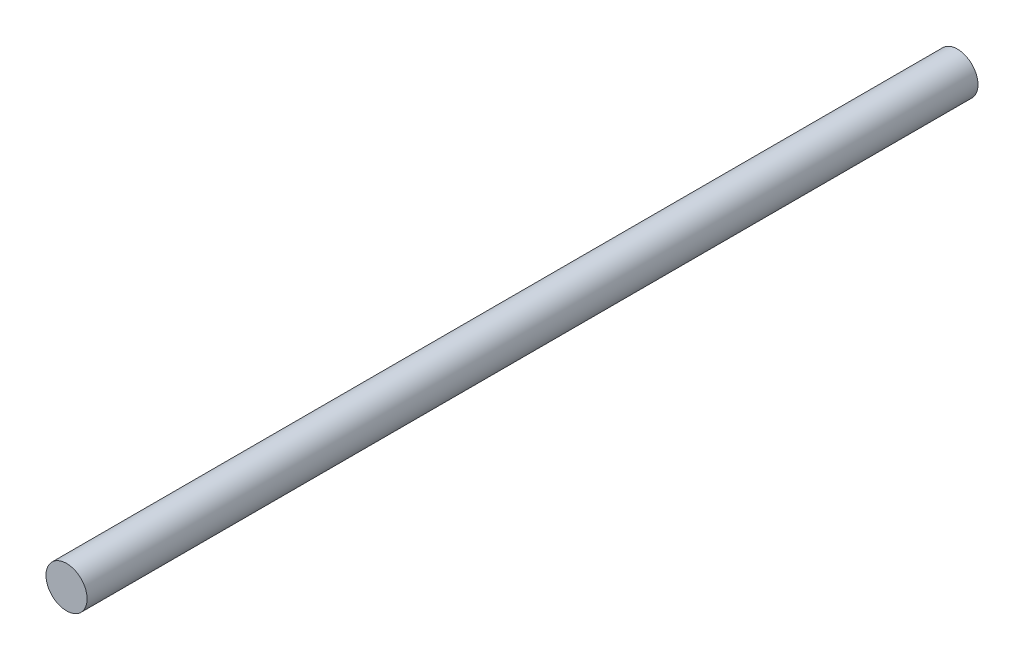
SolidWorks part; units mm, degrees
material "Plain Carbon Steel"
ref_plane "Front Plane" through (0, 0, 0) normal (0, 0, 1) x (1, 0, 0)
ref_plane "Top Plane" through (0, 0, 0) normal (0, 1, 0) x (1, 0, 0)
ref_plane "Right Plane" through (0, 0, 0) normal (1, 0, 0) x (0, 0, -1)
sketch "Sketch1" plane through (0, 0, 0) normal (0, 0, 1) x (1, 0, 0)
  circle A0 centre (0, 0) radius 6.35
  dimension "D1" = 12.7
extrude "Extrude1" add sketch "Sketch1" along normal mid plane 274.9017
